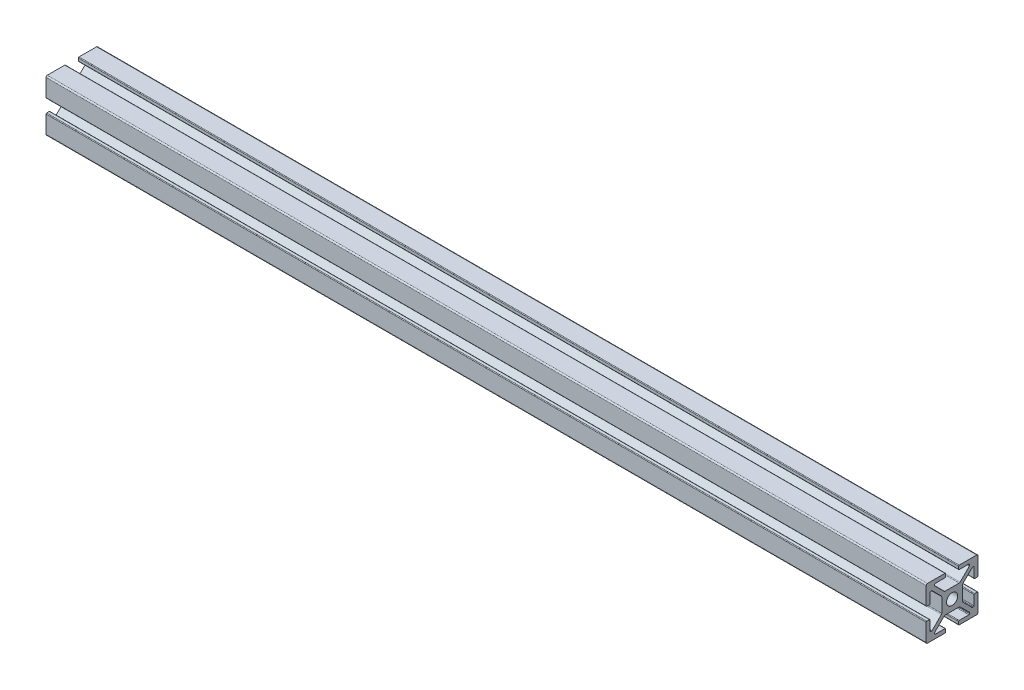
SolidWorks part; units mm, degrees
ref_plane "Спереди" through (0, 0, 0) normal (0, 0, 1) x (1, 0, 0)
ref_plane "Сверху" through (0, 0, 0) normal (0, 1, 0) x (1, 0, 0)
ref_plane "Справа" through (0, 0, 0) normal (1, 0, 0) x (0, 0, -1)
sketch "Эскиз1" plane through (0, 0, 170) normal (-1, 0, 0) x (0, 0, 1)
  line L0 (-10, -2.75) -> (-10, -9.5)
  line L1 (-9.5, -10) -> (-2.75, -10)
  line L2 (-2.5, -9.75) -> (-2.5, -8.75)
  line L3 (-2.75, -8.5) -> (-6.5, -8.5)
  line L4 (-6.75, -8.25) -> (-6.75, -7.9142)
  line L5 (-6.6768, -7.7374) -> (-3.0858, -4.1464)
  line L6 (-2.7322, -4) -> (2.7322, -4)
  line L7 (3.0858, -4.1464) -> (6.6768, -7.7374)
  line L8 (6.75, -7.9142) -> (6.75, -8.25)
  line L9 (6.5, -8.5) -> (2.75, -8.5)
  line L10 (2.5, -8.75) -> (2.5, -9.75)
  line L11 (2.75, -10) -> (9.5, -10)
  line L12 (10, -9.5) -> (10, -2.75)
  line L13 (9.75, -2.5) -> (8.75, -2.5)
  line L14 (8.5, -2.75) -> (8.5, -6.5)
  line L15 (8.25, -6.75) -> (7.9142, -6.75)
  line L16 (7.7374, -6.6768) -> (4.1464, -3.0858)
  line L17 (4, -2.7322) -> (4, 2.7322)
  line L18 (4.1464, 3.0858) -> (7.7374, 6.6768)
  line L19 (7.9142, 6.75) -> (8.25, 6.75)
  line L20 (8.5, 6.5) -> (8.5, 2.75)
  line L21 (8.75, 2.5) -> (9.75, 2.5)
  line L22 (10, 2.75) -> (10, 9.5)
  line L23 (9.5, 10) -> (2.75, 10)
  line L24 (2.5, 9.75) -> (2.5, 8.75)
  line L25 (2.75, 8.5) -> (6.5, 8.5)
  line L26 (6.75, 8.25) -> (6.75, 7.8107)
  line L27 (6.75, 7.8107) -> (3.0126, 4.0732)
  line L28 (2.8358, 4) -> (-2.7322, 4)
  line L29 (-3.0858, 4.1464) -> (-6.6768, 7.7374)
  line L30 (-6.75, 7.9142) -> (-6.75, 8.25)
  line L31 (-6.5, 8.5) -> (-2.75, 8.5)
  line L32 (-2.5, 8.75) -> (-2.5, 9.75)
  line L33 (-2.75, 10) -> (-9.5, 10)
  line L34 (-10, 9.5) -> (-10, 2.75)
  line L35 (-9.75, 2.5) -> (-8.75, 2.5)
  line L36 (-8.5, 2.75) -> (-8.5, 6.5)
  line L37 (-8.25, 6.75) -> (-7.9142, 6.75)
  line L38 (-7.7374, 6.6768) -> (-4.1464, 3.0858)
  line L39 (-4, 2.7322) -> (-4, -2.7322)
  line L40 (-4.1464, -3.0858) -> (-7.7374, -6.6768)
  line L41 (-7.9142, -6.75) -> (-8.25, -6.75)
  line L42 (-8.5, -6.5) -> (-8.5, -2.75)
  line L43 (-8.75, -2.5) -> (-9.75, -2.5)
  circle A0 centre (0, 0) radius 2.15
  arc A1 (-10, -9.5) -> (-9.5, -10) centre (-9.5, -9.5) ccw
  arc A2 (-2.75, -10) -> (-2.5, -9.75) centre (-2.75, -9.75) ccw
  arc A3 (-2.5, -8.75) -> (-2.75, -8.5) centre (-2.75, -8.75) ccw
  arc A4 (-6.5, -8.5) -> (-6.75, -8.25) centre (-6.5, -8.25) cw
  arc A5 (-6.75, -7.9142) -> (-6.6768, -7.7374) centre (-6.5, -7.9142) cw
  arc A6 (-3.0858, -4.1464) -> (-2.7322, -4) centre (-2.7322, -4.5) cw
  arc A7 (2.7322, -4) -> (3.0858, -4.1464) centre (2.7322, -4.5) cw
  arc A8 (6.6768, -7.7374) -> (6.75, -7.9142) centre (6.5, -7.9142) cw
  arc A9 (6.75, -8.25) -> (6.5, -8.5) centre (6.5, -8.25) cw
  arc A10 (2.75, -8.5) -> (2.5, -8.75) centre (2.75, -8.75) ccw
  arc A11 (2.5, -9.75) -> (2.75, -10) centre (2.75, -9.75) ccw
  arc A12 (9.5, -10) -> (10, -9.5) centre (9.5, -9.5) ccw
  arc A13 (10, -2.75) -> (9.75, -2.5) centre (9.75, -2.75) ccw
  arc A14 (8.75, -2.5) -> (8.5, -2.75) centre (8.75, -2.75) ccw
  arc A15 (8.5, -6.5) -> (8.25, -6.75) centre (8.25, -6.5) cw
  arc A16 (7.9142, -6.75) -> (7.7374, -6.6768) centre (7.9142, -6.5) cw
  arc A17 (4.1464, -3.0858) -> (4, -2.7322) centre (4.5, -2.7322) cw
  arc A18 (4, 2.7322) -> (4.1464, 3.0858) centre (4.5, 2.7322) cw
  arc A19 (7.7374, 6.6768) -> (7.9142, 6.75) centre (7.9142, 6.5) cw
  arc A20 (8.25, 6.75) -> (8.5, 6.5) centre (8.25, 6.5) cw
  arc A21 (8.5, 2.75) -> (8.75, 2.5) centre (8.75, 2.75) ccw
  arc A22 (9.75, 2.5) -> (10, 2.75) centre (9.75, 2.75) ccw
  arc A23 (10, 9.5) -> (9.5, 10) centre (9.5, 9.5) ccw
  arc A24 (2.75, 10) -> (2.5, 9.75) centre (2.75, 9.75) ccw
  arc A25 (2.5, 8.75) -> (2.75, 8.5) centre (2.75, 8.75) ccw
  arc A26 (6.5, 8.5) -> (6.75, 8.25) centre (6.5, 8.25) cw
  arc A27 (3.0126, 4.0732) -> (2.8358, 4) centre (2.8358, 4.25) cw
  arc A28 (-2.7322, 4) -> (-3.0858, 4.1464) centre (-2.7322, 4.5) cw
  arc A29 (-6.6768, 7.7374) -> (-6.75, 7.9142) centre (-6.5, 7.9142) cw
  arc A30 (-6.75, 8.25) -> (-6.5, 8.5) centre (-6.5, 8.25) cw
  arc A31 (-2.75, 8.5) -> (-2.5, 8.75) centre (-2.75, 8.75) ccw
  arc A32 (-2.5, 9.75) -> (-2.75, 10) centre (-2.75, 9.75) ccw
  arc A33 (-9.5, 10) -> (-10, 9.5) centre (-9.5, 9.5) ccw
  arc A34 (-10, 2.75) -> (-9.75, 2.5) centre (-9.75, 2.75) ccw
  arc A35 (-8.75, 2.5) -> (-8.5, 2.75) centre (-8.75, 2.75) ccw
  arc A36 (-8.5, 6.5) -> (-8.25, 6.75) centre (-8.25, 6.5) cw
  arc A37 (-7.9142, 6.75) -> (-7.7374, 6.6768) centre (-7.9142, 6.5) cw
  arc A38 (-4.1464, 3.0858) -> (-4, 2.7322) centre (-4.5, 2.7322) cw
  arc A39 (-4, -2.7322) -> (-4.1464, -3.0858) centre (-4.5, -2.7322) cw
  arc A40 (-7.7374, -6.6768) -> (-7.9142, -6.75) centre (-7.9142, -6.5) cw
  arc A41 (-8.25, -6.75) -> (-8.5, -6.5) centre (-8.25, -6.5) cw
  arc A42 (-8.5, -2.75) -> (-8.75, -2.5) centre (-8.75, -2.75) ccw
  arc A43 (-9.75, -2.5) -> (-10, -2.75) centre (-9.75, -2.75) ccw
extrude "Бобышка-Вытянуть1" add sketch "Эскиз1" against normal blind 340
